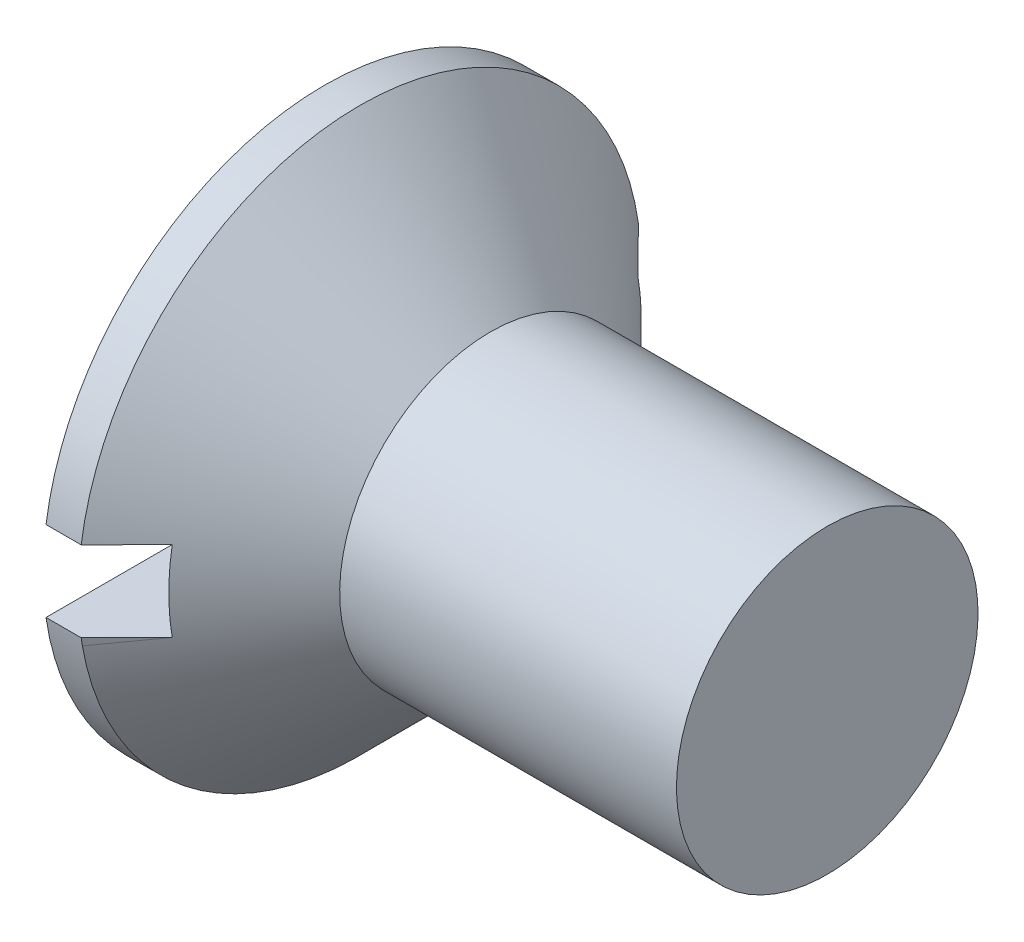
SolidWorks part; units mm, degrees
material "Plain Carbon Steel"
ref_plane "Front Plane" through (0, 0, 0) normal (0, 0, 1) x (1, 0, 0)
ref_plane "Top Plane" through (0, 0, 0) normal (0, 1, 0) x (1, 0, 0)
ref_plane "Right Plane" through (0, 0, 0) normal (1, 0, 0) x (0, 0, -1)
sketch "Sketch1" plane through (0, 0, 0) normal (0, 0, 1) x (1, 0, 0)
  line L0 (0, 0) -> (0, 2.8)
  line L1 (0, 2.8) -> (0.35, 2.8)
  line L2 (0.35, 2.8) -> (1.65, 1.5)
  line L3 (1.65, 1.5) -> (5, 1.5)
  line L4 (5, 1.5) -> (5, 0)
  line L5 (5, 0) -> (0, 0) construction
  line L6 (0, 0) -> (5, 0)
  dimension "D1" = 45
  dimension "D2" = 3
  dimension "D3" = 5.6
  dimension "D4" = 1.65
  dimension "D5" = 5
revolve "Revolve1" add sketch "Sketch1" angle 360 about L5
sketch "Sketch2" plane through (0, 0, 0) normal (-1, 0, 0) x (0, 0, 1)
  line L0 (2.8, 0) -> (-2.8, 0) construction
  line L1 (-2.8, 0.4) -> (2.8, 0.4)
  line L2 (-2.8, 0.4) -> (-2.8, -0.4)
  line L3 (-2.8, -0.4) -> (2.8, -0.4)
  line L4 (2.8, 0.4) -> (2.8, -0.4)
  circle A0 centre (0, 0) radius 2.8 construction
  dimension "D1" = 0.8
extrude "Cut-Extrude1" cut sketch "Sketch2" against normal blind 0.8
